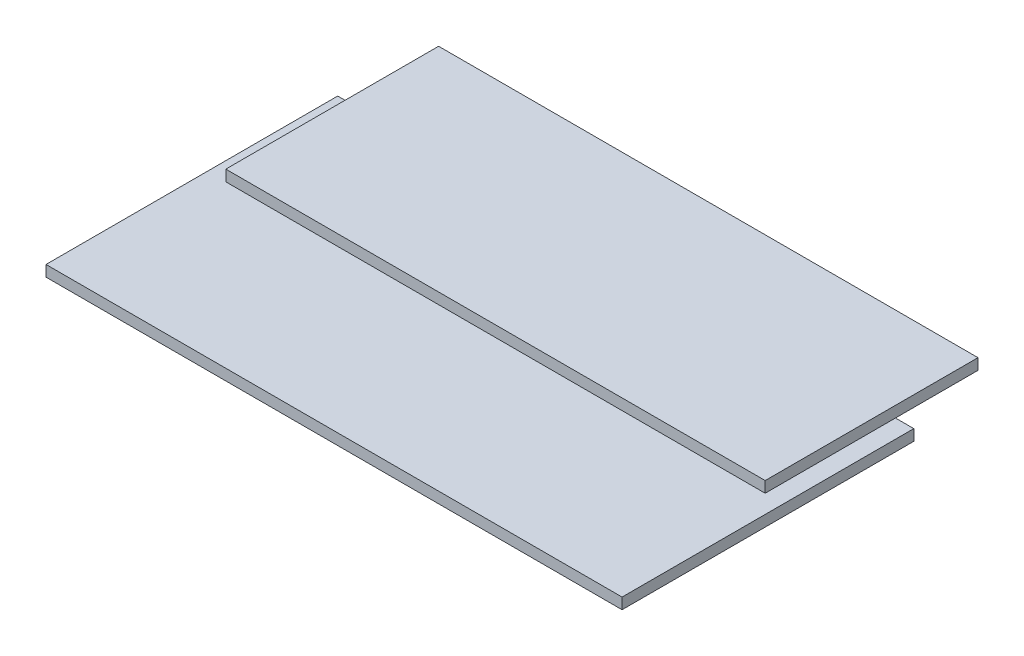
SolidWorks part; units mm, degrees
ref_plane "Front Plane" through (0, 0, 0) normal (0, 0, 1) x (1, 0, 0)
ref_plane "Top Plane" through (0, 0, 0) normal (0, 1, 0) x (1, 0, 0)
ref_plane "Right Plane" through (0, 0, 0) normal (1, 0, 0) x (0, 0, -1)
sketch "Sketch2" plane through (0, 0, 0) normal (0, 1, 0) x (1, 0, 0)
  line L1 (-39.25, 19.8768) -> (39.25, 19.8768)
  line L2 (-39.25, 19.8768) -> (-39.25, -19.8768)
  line L3 (-39.25, -19.8768) -> (39.25, -19.8768)
  line L4 (39.25, 19.8768) -> (39.25, -19.8768)
  line L5 (-39.25, 19.8768) -> (39.25, -19.8768) construction
  line L6 (-39.25, -19.8768) -> (39.25, 19.8768) construction
  point P0 (0, 0)
  dimension "D1" = 78.5
extrude "Boss-Extrude1" add sketch "Sketch2" along normal mid plane 1.5
sketch "Sketch3" plane through (0, 0.75, 0) normal (0, 1, 0) x (1, 0, 0)
  line L0 (39.25, -19.8768) -> (39.25, 2.1232) construction
  line L1 (39.25, -19.8768) -> (39.25, 19.8768) construction
  line L2 (36.75, 2.1232) -> (39.25, 2.1232) construction
  line L3 (36.75, 2.1232) -> (-36.75, 2.1232)
  line L4 (36.75, 2.1232) -> (36.75, 31.1232)
  line L5 (36.75, 31.1232) -> (-36.75, 31.1232)
  line L6 (-36.75, 2.1232) -> (-36.75, 31.1232)
  line L7 (-36.75, 2.1232) -> (-39.25, 2.1232) construction
  line L8 (-39.25, 19.8768) -> (-39.25, -19.8768) construction
  dimension "D1" = 22
  dimension "D2" = 2.5
  dimension "D3" = 29
extrude "Boss-Extrude2" add sketch "Sketch3" along normal blind 1.5
